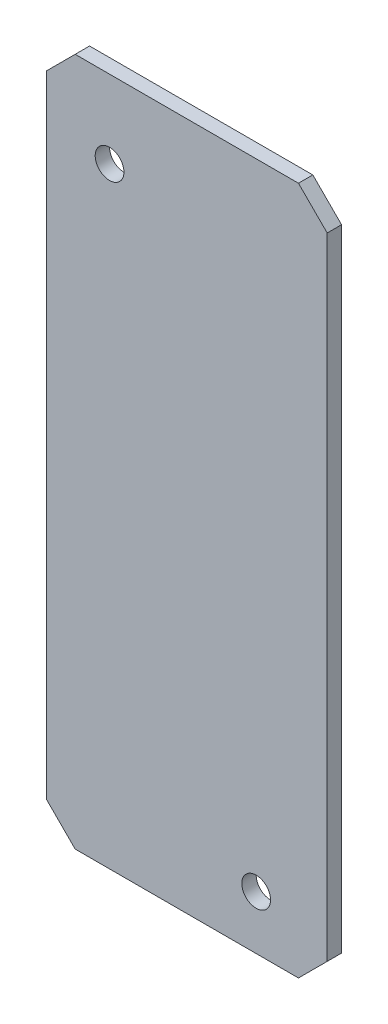
SolidWorks part; units mm, degrees
ref_plane "Plan de face" through (0, 0, 0) normal (0, 0, 1) x (1, 0, 0)
ref_plane "Plan de dessus" through (0, 0, 0) normal (0, 1, 0) x (1, 0, 0)
ref_plane "Plan de droite" through (0, 0, 0) normal (1, 0, 0) x (0, 0, -1)
sketch "Esquisse1" plane through (0, 0, 0) normal (0, 0, 1) x (1, 0, 0)
  line L1 (-51.866, -36.6137) -> (-32.3255, -36.6137)
  line L2 (-51.866, -36.6137) -> (-51.866, -84.5189)
  line L3 (-51.866, -84.5189) -> (-32.3255, -84.5189)
  line L4 (-32.3255, -36.6137) -> (-32.3255, -84.5189)
  circle A0 centre (-37.2688, -80.7891) radius 1 construction
  circle A1 centre (-47.4715, -42.0224) radius 1 construction
  circle A2 centre (-37.2688, -80.7891) radius 1
  circle A3 centre (-47.4715, -42.0224) radius 1
extrude "Extrusion1" add sketch "Esquisse1" along normal blind 1
chamfer "Chanfrein1" distance 2 angle 45 4 edges at (-51.866, -84.5189, 0.5) (-32.3255, -84.5189, 0.5) (-32.3255, -36.6137, 0.5) (-51.866, -36.6137, 0.5)
